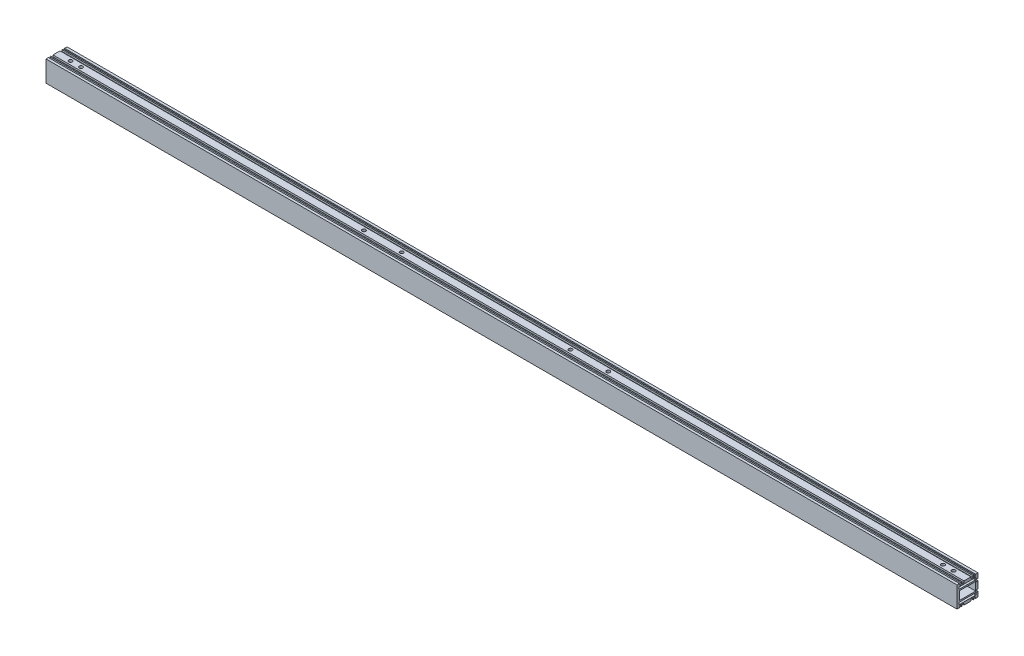
SolidWorks part; units mm, degrees
ref_plane "前视基准面" through (0, 0, 0) normal (0, 0, 1) x (1, 0, 0)
ref_plane "上视基准面" through (0, 0, 0) normal (0, 1, 0) x (1, 0, 0)
ref_plane "右视基准面" through (0, 0, 0) normal (1, 0, 0) x (0, 0, -1)
sketch "草图1" plane through (0, 0, 0) normal (1, 0, 0) x (0, 0, -1)
  line L0 (-15, 15) -> (15, -15) construction
  line L1 (-15, 15) -> (-11.5, 15)
  line L2 (-15, 15) -> (-15, -15)
  line L3 (-15, -15) -> (-11.5, -15)
  line L4 (15, 15) -> (15, 8)
  line L5 (15, 15) -> (-15, -15) construction
  line L6 (-11.5, 15) -> (-11.5, 13.5)
  line L7 (-11.5, 13.5) -> (-11, 13.5)
  line L8 (-11, 13.5) -> (-11, 12)
  line L9 (-11, 12) -> (-9.5, 12)
  line L10 (-9.5, 12) -> (-9.5, 15)
  line L11 (-9.5, 15) -> (-8, 15)
  line L12 (-8, 15) -> (-8, 12.5)
  line L13 (-8, 12.5) -> (-5, 12.5)
  line L14 (-5, 12.5) -> (-5, 15)
  line L15 (-5, 15) -> (5, 15)
  line L16 (0, 21.5201) -> (0, -18.309) construction
  line L17 (0, 55) -> (0, -55) construction
  line L18 (5, 12.5) -> (5, 15)
  line L19 (8, 12.5) -> (5, 12.5)
  line L20 (8, 15) -> (8, 12.5)
  line L21 (9.5, 15) -> (8, 15)
  line L22 (9.5, 12) -> (9.5, 15)
  line L23 (11, 12) -> (9.5, 12)
  line L24 (11, 13.5) -> (11, 12)
  line L25 (11.5, 13.5) -> (11, 13.5)
  line L26 (11.5, 15) -> (11.5, 13.5)
  line L27 (8, 15) -> (9.5, 15)
  line L28 (11.5, 15) -> (15, 15)
  line L29 (-19.8303, 0) -> (22.13, 0) construction
  line L30 (55, 0) -> (-55, 0) construction
  line L31 (8, -15) -> (9.5, -15)
  line L32 (11.5, -15) -> (11.5, -13.5)
  line L33 (11.5, -13.5) -> (11, -13.5)
  line L34 (11, -13.5) -> (11, -12)
  line L35 (11, -12) -> (9.5, -12)
  line L36 (9.5, -12) -> (9.5, -15)
  line L37 (9.5, -15) -> (8, -15)
  line L38 (8, -15) -> (8, -12.5)
  line L39 (8, -12.5) -> (5, -12.5)
  line L40 (5, -12.5) -> (5, -15)
  line L41 (-5, -15) -> (5, -15)
  line L42 (-5, -12.5) -> (-5, -15)
  line L43 (-8, -12.5) -> (-5, -12.5)
  line L44 (-8, -15) -> (-8, -12.5)
  line L45 (-9.5, -15) -> (-8, -15)
  line L46 (-9.5, -12) -> (-9.5, -15)
  line L47 (-11, -12) -> (-9.5, -12)
  line L48 (-11, -13.5) -> (-11, -12)
  line L49 (-11.5, -13.5) -> (-11, -13.5)
  line L50 (-11.5, -15) -> (-11.5, -13.5)
  line L51 (-9.5, -15) -> (-8, -15)
  line L52 (-5, -15) -> (5, -15)
  line L53 (8, -15) -> (9.5, -15)
  line L54 (11.5, -15) -> (15, -15)
  line L55 (15, 8) -> (12.5, 8)
  line L56 (12.5, 8) -> (12.5, 5)
  line L57 (12.5, 5) -> (15, 5)
  line L58 (12.5, -5) -> (15, -5)
  line L59 (12.5, -8) -> (12.5, -5)
  line L60 (15, -8) -> (12.5, -8)
  line L61 (15, 5) -> (15, -5)
  line L62 (15, -8) -> (15, -15)
  line L63 (12, -10.5) -> (12, -8.5)
  line L64 (-11.5, 11) -> (11.5, 11)
  line L65 (-12, 10.5) -> (-12, 8.5)
  line L66 (-11.5, 8) -> (11.5, 8)
  line L67 (12, 10.5) -> (12, 8.5)
  line L68 (-11.5, -8) -> (11.5, -8)
  line L69 (-12, -10.5) -> (-12, -8.5)
  line L70 (-11.5, -11) -> (11.5, -11)
  line L72 (-11.75, 6) -> (11.75, 6)
  line L73 (-11.75, 6) -> (-11.75, -6)
  line L74 (-11.75, -6) -> (11.75, -6)
  line L75 (11.75, 6) -> (11.75, -6)
  arc A0 (12, 8.5) -> (11.5, 8) centre (11.5, 8.5) cw
  arc A1 (11.5, 11) -> (12, 10.5) centre (11.5, 10.5) cw
  arc A2 (-11.5, 11) -> (-12, 10.5) centre (-11.5, 10.5) ccw
  arc A3 (-11.5, 8) -> (-12, 8.5) centre (-11.5, 8.5) cw
  arc A8 (-11.5, -8) -> (-12, -8.5) centre (-11.5, -8.5) ccw
  arc A9 (-11.5, -11) -> (-12, -10.5) centre (-11.5, -10.5) cw
  arc A10 (11.5, -11) -> (12, -10.5) centre (11.5, -10.5) ccw
  arc A11 (12, -8.5) -> (11.5, -8) centre (11.5, -8.5) ccw
  point P69 (12, 11)
  point P72 (-12, 11)
  point P77 (-11, -13.5)
  point P80 (11, -13.5)
  point P83 (11, 13.5)
  point P86 (-11, 13.5)
  point P99 (-12, -11)
  point P100 (12, -11)
  dimension "D17" = 0.5
  dimension "D1" = 3.5
  dimension "D2" = 1.5
  dimension "D3" = 0.5
  dimension "D4" = 1.5
  dimension "D5" = 3
  dimension "D6" = 30
  dimension "D7" = 30
  dimension "D8" = 1.5
  dimension "D9" = 2.5
  dimension "D10" = 3
  dimension "D11" = 2.5
  dimension "D12" = 7
  dimension "D13" = 3
  dimension "D14" = 4
  dimension "D15" = 3
  dimension "D16" = 24
  dimension "D19" = 23.5
  dimension "D20" = 12
extrude "凸台-拉伸1" add sketch "草图1" along normal mid plane 1301
hole_wizard "M6 螺纹孔1" positions "草图3" profile "草图2" tap size "M6" standard "GB"
sketch "草图3" plane through (0, 15, 0) normal (0, 1, 0) x (1, 0, 0)
  line L0 (650.5, -15) -> (-650.5, -15) construction
  line L1 (-650.5, -5) -> (-650.5, 5) construction
  line L2 (650.5, -5) -> (650.5, 5) construction
  point P0 (-630.5, 0)
  point P3 (-615.5, 0)
  point P6 (615.5, 0)
  point P9 (630.5, 0)
  point P12 (-211.5, 0)
  point P14 (-157.5, 0)
  point P20 (83.5, 0)
  point P22 (137.5, 0)
  dimension "D1" = 15
  dimension "D2" = 15
  dimension "D3" = 493
  dimension "D4" = 439
  dimension "D5" = 15
  dimension "D6" = 15
  dimension "D7" = 513
  dimension "D8" = 567
sketch "草图2" plane through (-630.5, 15, 0) normal (1, 0, 0) x (0, 0, 1)
  line L0 (0, 0) -> (0, 20.5022)
  line L1 (0, 20.5022) -> (2.5, 19)
  line L2 (2.5, 19) -> (2.5, 0)
  line L5 (2.5, 0) -> (0, 0)
  line L10 (0, 20.5022) -> (-2.5, 19) construction
  line L11 (0, -6.35) -> (0, 107.95) construction
  dimension "螺纹孔钻头直径" = 5
  dimension "螺纹孔钻头深度" = 19
  dimension "导头角度" = 118
cosmetic thread "孔螺蚊线1" parameters "D1"=9, "D2"=6
cosmetic thread "孔螺蚊线2" parameters "D1"=9, "D2"=6
cosmetic thread "孔螺蚊线3" parameters "D1"=9, "D2"=6
cosmetic thread "孔螺蚊线4" parameters "D1"=9, "D2"=6
cosmetic thread "孔螺蚊线5" parameters "D1"=9, "D2"=6
cosmetic thread "孔螺蚊线6" parameters "D1"=9, "D2"=6
cosmetic thread "孔螺蚊线7" parameters "D1"=9, "D2"=6
cosmetic thread "孔螺蚊线8" parameters "D1"=9, "D2"=6
hole_wizard "M6 螺纹孔2" positions "草图5" profile "草图4" tap size "M6" standard "GB"
sketch "草图5" plane through (0, 0, -15) normal (0, 0, -1) x (-1, 0, 0)
  line L0 (-650.5, -15) -> (650.5, -15) construction
  line L1 (650.5, -8) -> (650.5, -15) construction
  line L2 (650.5, 5) -> (650.5, -5) construction
  point P0 (133.5, 0)
  point P2 (-6.5, 0)
  dimension "D1" = 15
  dimension "D2" = 15
  dimension "D3" = 657
  dimension "D4" = 517
sketch "草图4" plane through (-133.5, 0, -15) normal (1, 0, 0) x (0, 1, 0)
  line L0 (0, 0) -> (0, 20.5022)
  line L1 (0, 20.5022) -> (2.5, 19)
  line L2 (2.5, 19) -> (2.5, 0)
  line L5 (2.5, 0) -> (0, 0)
  line L10 (0, 20.5022) -> (-2.5, 19) construction
  line L11 (0, -6.35) -> (0, 107.95) construction
  dimension "螺纹孔钻头直径" = 5
  dimension "螺纹孔钻头深度" = 19
  dimension "导头角度" = 118
cosmetic thread "孔螺蚊线9" parameters "D1"=3.25, "D2"=6
cosmetic thread "孔螺蚊线10" parameters "D1"=3.25, "D2"=6
hole_wizard "M4 螺纹孔1" positions "草图7" profile "草图6" tap size "M4" standard "GB"
sketch "草图7" plane through (0, 0, -15) normal (0, 0, -1) x (-1, 0, 0)
  line L0 (-650.5, -15) -> (650.5, -15) construction
  line L1 (-650.5, -8) -> (-650.5, -15) construction
  point P0 (-312, 0)
  dimension "D1" = 15
  dimension "D2" = 338.5
sketch "草图6" plane through (312, 0, -15) normal (1, 0, 0) x (0, 1, 0)
  line L0 (0, 0) -> (0, 12.4914)
  line L1 (0, 12.4914) -> (1.65, 11.5)
  line L2 (1.65, 11.5) -> (1.65, 0)
  line L5 (1.65, 0) -> (0, 0)
  line L10 (0, 12.4914) -> (-1.65, 11.5) construction
  line L11 (0, -6.35) -> (0, 107.95) construction
  dimension "螺纹孔钻头直径" = 3.3
  dimension "螺纹孔钻头深度" = 11.5
  dimension "导头角度" = 118
cosmetic thread "孔螺蚊线11" parameters "D1"=3.25, "D2"=4
